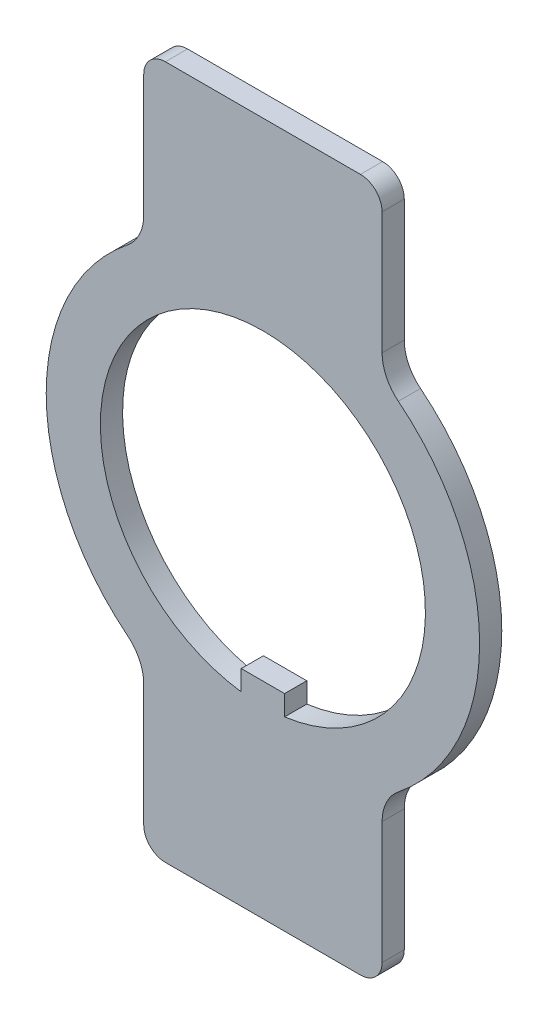
SolidWorks part; units mm, degrees
ref_plane "Front Plane" through (0, 0, 0) normal (0, 0, 1) x (1, 0, 0)
ref_plane "Top Plane" through (0, 0, 0) normal (0, 1, 0) x (1, 0, 0)
ref_plane "Right Plane" through (0, 0, 0) normal (1, 0, 0) x (0, 0, -1)
sketch "Sketch1" plane through (0, 0, 0) normal (0, 0, 1) x (1, 0, 0)
  line L0 (0, 12.7) -> (0, -12.7) construction
  line L1 (-7.9375, 0) -> (7.9375, 0) construction
  line L2 (-4.3656, 12.7) -> (4.3656, 12.7)
  line L3 (-4.3656, 12.7) -> (-4.3656, 6.6291)
  line L4 (-4.3656, -12.7) -> (4.3656, -12.7)
  line L5 (4.3656, -12.7) -> (4.3656, -6.6291)
  line L6 (-4.3656, -6.6291) -> (-4.3656, -12.7)
  line L7 (4.3656, 6.6291) -> (4.3656, 12.7)
  line L8 (-0.7937, -5.9) -> (-0.7937, -5.1594)
  line L9 (-0.7937, -5.1594) -> (0.7938, -5.1594)
  line L10 (0.7938, -5.1594) -> (0.7938, -5.9)
  circle A0 centre (0, 0) radius 5.9531 construction
  arc A2 (-4.3656, 6.6291) -> (-4.3656, -6.6291) centre (0, 0) ccw
  arc A3 (4.3656, -6.6291) -> (4.3656, 6.6291) centre (0, 0) ccw
  arc A4 (-0.7937, -5.9) -> (0.7938, -5.9) centre (0, 0) cw
  dimension "D1" = 11.9062
  dimension "D2" = 25.4
  dimension "D3" = 15.875
  dimension "D5" = 8.7312
  dimension "D6" = 0.7937
  dimension "D7" = 1.5875
extrude "Boss-Extrude1" add sketch "Sketch1" along normal blind 0.8128
fillet "Fillet1" radius 0.7937 4 edges at (-4.3656, 12.7, 0.4064) (4.3656, 12.7, 0.4064) (4.3656, -12.7, 0.4064) (-4.3656, -12.7, 0.4064)
fillet "Fillet2" radius 1.5875 4 edges at (-4.3656, 6.6291, 0.4064) (4.3656, 6.6291, 0.4064) (4.3656, -6.6291, 0.4064) (-4.3656, -6.6291, 0.4064)
